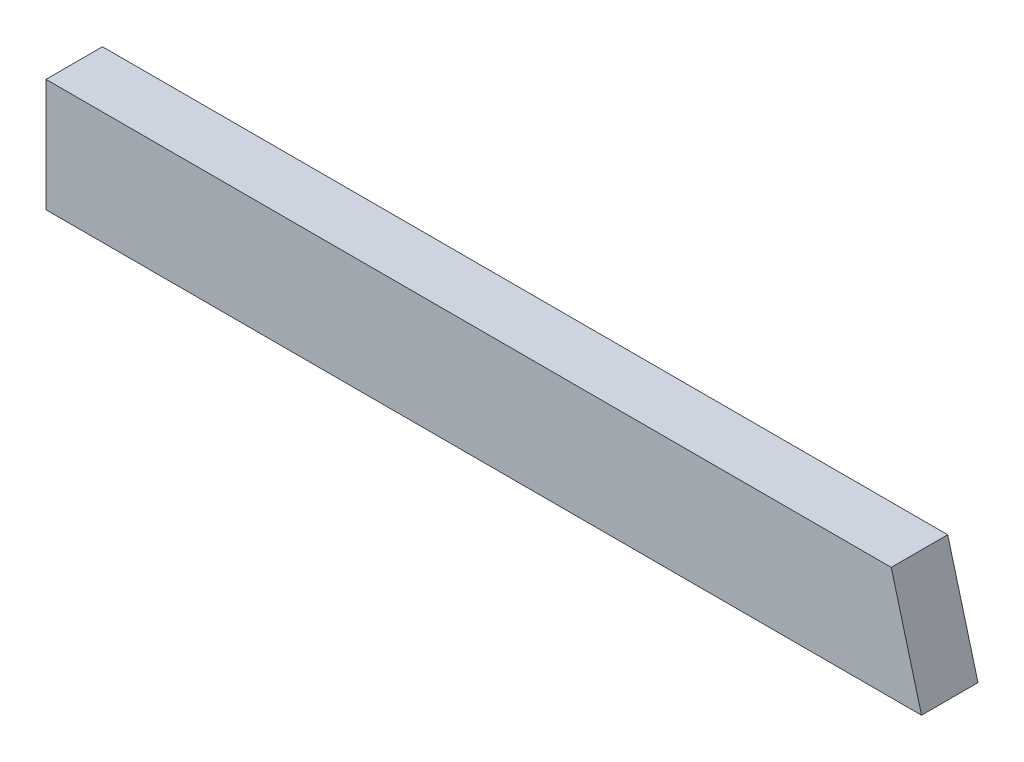
SolidWorks part; units mm, degrees
ref_plane "Front Plane" through (0, 0, 0) normal (0, 0, 1) x (1, 0, 0)
ref_plane "Top Plane" through (0, 0, 0) normal (0, 1, 0) x (1, 0, 0)
ref_plane "Right Plane" through (0, 0, 0) normal (1, 0, 0) x (0, 0, -1)
sketch "Sketch1" plane through (0, 0, 0) normal (0, 0, 1) x (1, 0, 0)
  line L0 (787.4, 0) -> (760.1764, 101.6)
  line L1 (0, 0) -> (787.4, 0)
  line L2 (0, 0) -> (0, 101.6)
  line L3 (0, 101.6) -> (787.4, 101.6)
  line L4 (787.4, 0) -> (787.4, 101.6)
  dimension "D1" = 101.6
  dimension "D2" = 787.4
  dimension "D3" = 15
extrude "Boss-Extrude1" add sketch "Sketch1" along normal blind 50.8 contours L3 L2 L1 L0
